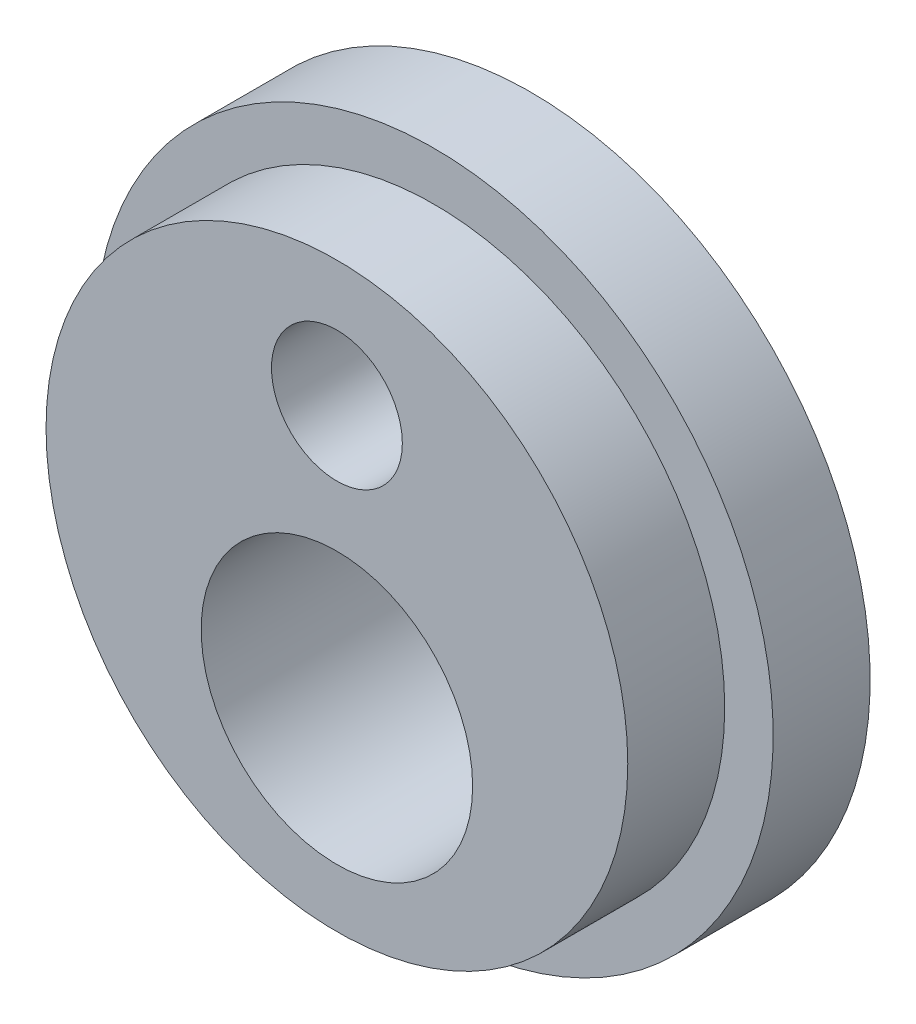
SolidWorks part; units mm, degrees
ref_plane "Front Plane" through (0, 0, 0) normal (0, 0, 1) x (1, 0, 0)
ref_plane "Top Plane" through (0, 0, 0) normal (0, 1, 0) x (1, 0, 0)
ref_plane "Right Plane" through (0, 0, 0) normal (1, 0, 0) x (0, 0, -1)
sketch "Sketch1" plane through (0, 0, 0) normal (0, 0, 1) x (1, 0, 0)
  circle A0 centre (0, 0) radius 44.45
  dimension "D1" = 88.9
extrude "Boss-Extrude1" add sketch "Sketch1" along normal blind 12.7
sketch "Sketch2" plane through (0, 0, 12.7) normal (0, 0, 1) x (1, 0, 0)
  circle A0 centre (0, 0) radius 38.1
  dimension "D1" = 76.2
extrude "Boss-Extrude2" add sketch "Sketch2" along normal blind 12.7
sketch "Sketch3" plane through (0, 0, 25.4) normal (0, 0, 1) x (1, 0, 0)
  circle A0 centre (0, 21.59) radius 8.5725
  dimension "D1" = 17.145
extrude "Cut-Extrude1" cut sketch "Sketch3" against normal through all both and the other way through all
sketch "Sketch4" plane through (0, 0, 25.4) normal (0, 0, 1) x (1, 0, 0)
  circle A0 centre (0, -12.7) radius 17.78
  dimension "D1" = 35.56
extrude "Cut-Extrude3" cut sketch "Sketch4" against normal through all both and the other way through all contours A0
sketch "Sketch5" plane through (0, 0, 0) normal (0, 0, -1) x (-1, 0, 0)
  circle A0 centre (27.94, -12.7) radius 3.175
  circle A1 centre (-27.94, -12.7) radius 3.175
  dimension "D1" = 6.35
  dimension "D2" = 6.35
extrude "Cut-Extrude4" cut sketch "Sketch5" against normal blind 12.7
